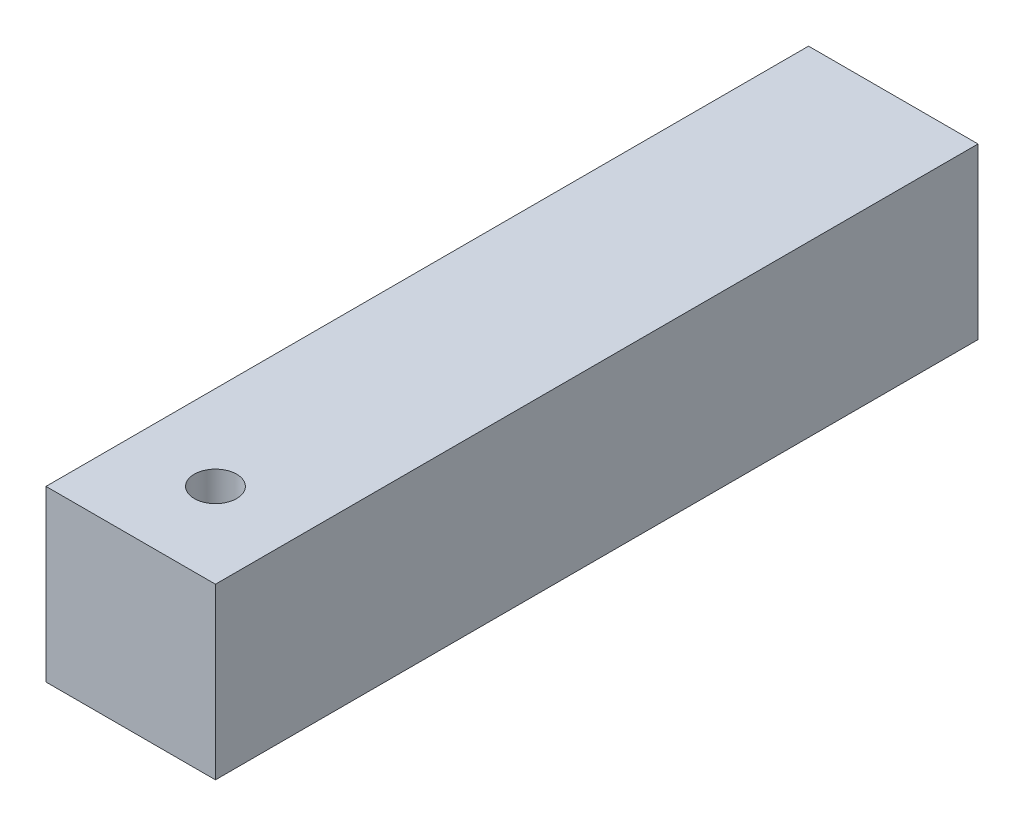
SolidWorks part; units mm, degrees
ref_plane "Front Plane" through (0, 0, 0) normal (0, 0, 1) x (1, 0, 0)
ref_plane "Top Plane" through (0, 0, 0) normal (0, 1, 0) x (1, 0, 0)
ref_plane "Right Plane" through (0, 0, 0) normal (1, 0, 0) x (0, 0, -1)
sketch "Sketch2" plane through (0, 0, 0) normal (0, 0, 1) x (1, 0, 0)
  line L1 (50, 50) -> (-50, 50)
  line L2 (50, 50) -> (50, -50)
  line L3 (50, -50) -> (-50, -50)
  line L4 (-50, 50) -> (-50, -50)
  line L5 (50, 50) -> (-50, -50) construction
  line L6 (50, -50) -> (-50, 50) construction
  point P0 (0, 0)
  dimension "D1" = 100
  dimension "D2" = 100
extrude "Boss-Extrude1" add sketch "Sketch2" against normal blind 450
sketch "Sketch3" plane through (0, 50, 0) normal (0, 1, 0) x (1, 0, 0)
  line L0 (0, 450) -> (0, 0) construction
  line L1 (50, 450) -> (-50, 450) construction
  circle A0 centre (0, 50) radius 12.5
  dimension "D1" = 25
  dimension "D2" = 400
extrude "Cut-Extrude1" cut sketch "Sketch3" against normal blind 500
